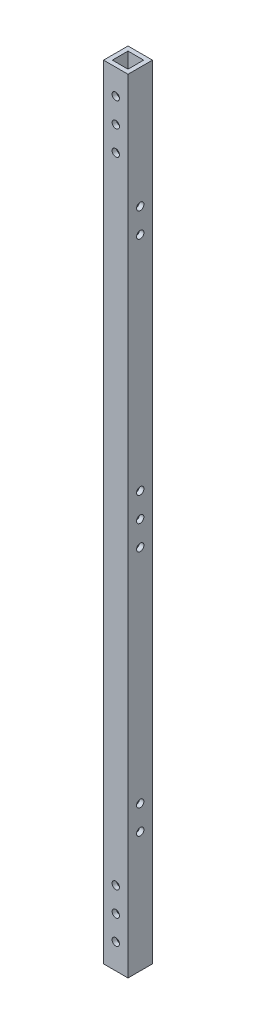
SolidWorks part; units mm, degrees
ref_plane "前视基准面" through (0, 0, 0) normal (0, 0, 1) x (1, 0, 0)
ref_plane "上视基准面" through (0, 0, 0) normal (0, 1, 0) x (1, 0, 0)
ref_plane "右视基准面" through (0, 0, 0) normal (1, 0, 0) x (0, 0, -1)
sketch "草图1" plane through (0, 0, 0) normal (0, 1, 0) x (1, 0, 0)
  line L1 (-5, 5) -> (5, 5)
  line L2 (-5, 5) -> (-5, -5)
  line L3 (-5, -5) -> (5, -5)
  line L4 (5, 5) -> (5, -5)
  line L5 (-5, 5) -> (5, -5) construction
  line L6 (-5, -5) -> (5, 5) construction
  line L7 (-3.2, 3.2) -> (3.2, 3.2)
  line L8 (-3.2, 3.2) -> (-3.2, -3.2)
  line L9 (-3.2, -3.2) -> (3.2, -3.2)
  line L10 (3.2, 3.2) -> (3.2, -3.2)
  line L11 (-3.2, 3.2) -> (3.2, -3.2) construction
  line L12 (-3.2, -3.2) -> (3.2, 3.2) construction
  point P0 (0, 0)
  point P6 (0, 0)
  dimension "D1" = 1.8
  dimension "D2" = 10
extrude "凸台-拉伸1" add sketch "草图1" along normal mid plane 320
sketch "草图2" plane through (0, 0, -5) normal (0, 0, -1) x (-1, 0, 0)
  line L0 (0, 0) -> (-31.6693, 0) construction
  line L1 (0, 6.5147) -> (0, -25.163) construction
  line L2 (-14.614, -119.7) -> (84.614, -119.7) construction
  circle A3 centre (0, -149.7) radius 1.5
  circle A4 centre (0, -139.7) radius 1.5
  circle A5 centre (0, -129.7) radius 1.5
  circle A6 centre (0, 139.7) radius 1.5
  circle A7 centre (0, 149.7) radius 1.5
  circle A8 centre (0, 129.7) radius 1.5
  dimension "D4" = 3
  dimension "D1" = 10
  dimension "D2" = 10
  dimension "D3" = 10
extrude "切除-拉伸1" cut sketch "草图2" against normal through all
sketch "草图3" plane through (-5, 0, 0) normal (-1, 0, 0) x (0, 0, 1)
  line L0 (0, 0) -> (-37.9958, 0) construction
  circle A0 centre (0, -110.7) radius 1.5
  circle A1 centre (0, -100.7) radius 1.5
  circle A2 centre (0, 100.7) radius 1.5
  circle A3 centre (0, 110.7) radius 1.5
  dimension "D1" = 3
extrude "切除-拉伸2" cut sketch "草图3" against normal through all
sketch "草图4" plane through (5, 0, 0) normal (1, 0, 0) x (0, 0, -1)
  circle A0 centre (0, 0) radius 1.5
  circle A1 centre (0, -10) radius 1.5
  circle A2 centre (0, 10) radius 1.5
extrude "切除-拉伸3" cut sketch "草图4" against normal through all
